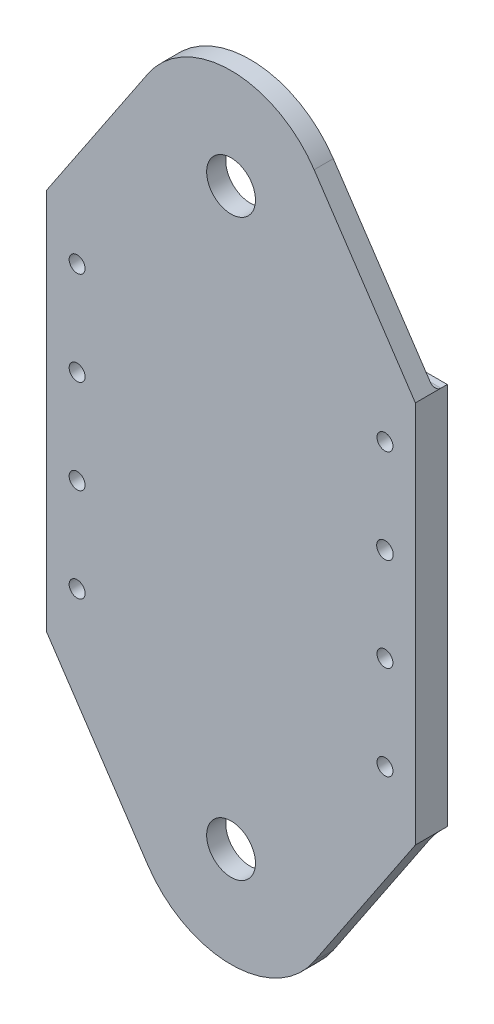
SolidWorks part; units mm, degrees
ref_plane "Front Plane" through (0, 0, 0) normal (0, 0, 1) x (1, 0, 0)
ref_plane "Top Plane" through (0, 0, 0) normal (0, 1, 0) x (1, 0, 0)
ref_plane "Right Plane" through (0, 0, 0) normal (1, 0, 0) x (0, 0, -1)
sketch "Sketch1" plane through (0, 0, 0) normal (0, 0, 1) x (1, 0, 0)
  line L1 (-34.2363, 0) -> (112.5008, 0)
  line L2 (-34.2363, 0) -> (-34.2363, -152.4)
  line L3 (-34.2363, -152.4) -> (112.5008, -152.4)
  line L4 (112.5008, 0) -> (112.5008, -152.4)
  circle A0 centre (-22.1315, -19.4469) radius 2.8149
extrude "Extrude1" add sketch "Sketch1" along normal blind 12.7
sketch "Sketch2" plane through (0, 0, -12.9013) normal (0, 0, -1) x (-1, 0, 0)
  circle A2 centre (-100.3959, -19.4469) radius 3.175
  circle A3 centre (-100.3959, -56.7531) radius 3.3017
  circle A4 centre (-100.3959, -94.0911) radius 3.175
  circle A5 centre (-100.3959, -131.4291) radius 3.175
  circle A6 centre (22.1315, -56.7531) radius 3.175
  circle A7 centre (22.1315, -94.0911) radius 3.175
  circle A8 centre (22.1315, -131.4291) radius 3.175
  circle A9 centre (22.1315, -19.4469) radius 3.175
  dimension "D2" = 6.35
extrude "Extrude2" cut sketch "Sketch2" against normal through all
ref_plane "Plane1" through (0, 0, 12.7) normal (0, 0, 1) x (1, 0, 0)
sketch "Sketch3" plane through (0, 0, 12.7) normal (0, 0, 1) x (1, 0, 0)
  line L0 (112.5008, -152.4) -> (-34.2363, -152.4)
  line L1 (112.5008, 0) -> (-34.2363, 0)
  line L2 (-34.2363, 0) -> (6.0556, 60.2279)
  line L3 (112.5008, 0) -> (72.2088, 60.2279)
  line L4 (-34.2363, -76.2) -> (112.5008, -76.2) construction
  line L5 (-34.2363, 0) -> (-34.2363, -152.4) construction
  line L6 (112.5008, -152.4) -> (112.5008, 0) construction
  line L7 (112.5008, -152.4) -> (72.2088, -212.6279)
  line L8 (-34.2363, -152.4) -> (6.0556, -212.6279)
  line L9 (-34.2363, -152.4) -> (112.5008, -152.4) construction
  arc A0 (72.2088, 60.2279) -> (6.0556, 60.2279) centre (39.1322, 38.1) ccw
  arc A1 (72.2088, -212.6279) -> (6.0556, -212.6279) centre (39.1322, -190.5) cw
  circle A2 centre (39.1322, 38.1) radius 9.7115
  circle A3 centre (39.1322, -190.5) radius 9.7115
  dimension "D1" = 38.1
  dimension "D2" = 38.1
extrude "Extrude3" add sketch "Sketch3" against normal blind 7.62
fillet "Fillet1" radius 2.54 2 edges
